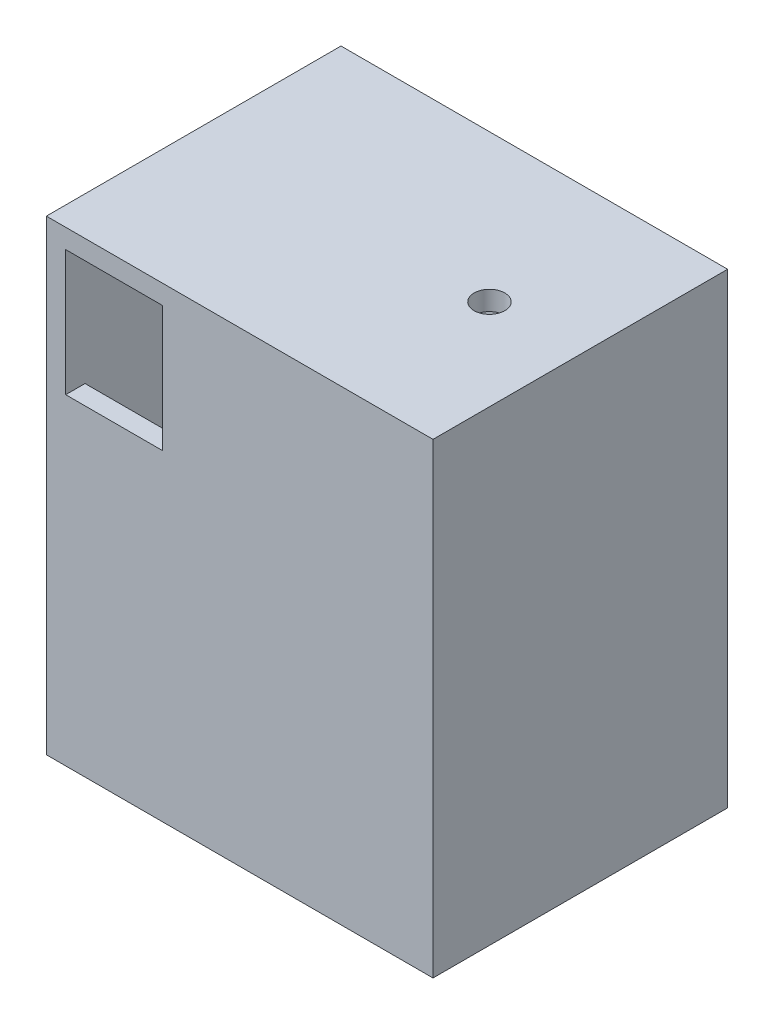
SolidWorks part; units mm, degrees
ref_plane "Front Plane" through (0, 0, 0) normal (0, 0, 1) x (1, 0, 0)
ref_plane "Top Plane" through (0, 0, 0) normal (0, 1, 0) x (1, 0, 0)
ref_plane "Right Plane" through (0, 0, 0) normal (1, 0, 0) x (0, 0, -1)
sketch "Sketch1" plane through (0, 0, 0) normal (0, 1, 0) x (1, 0, 0)
  line L1 (-200, 152.4) -> (200, 152.4)
  line L2 (-200, 152.4) -> (-200, -152.4)
  line L3 (-200, -152.4) -> (200, -152.4)
  line L4 (200, 152.4) -> (200, -152.4)
  line L5 (-200, 152.4) -> (200, -152.4) construction
  line L6 (-200, -152.4) -> (200, 152.4) construction
  point P0 (0, 0)
  dimension "D1" = 400
  dimension "D2" = 304.8
extrude "Boss-Extrude1" add sketch "Sketch1" along normal blind 482.6 contours L2 L3 L4 L1
shell "Shell1" thickness 20
sketch "Sketch2" plane through (0, 482.6, 0) normal (0, 1, 0) x (1, 0, 0)
  line L0 (-55, 0) -> (55, 0) construction
  line L1 (200, 152.4) -> (200, -152.4) construction
  circle A0 centre (106, 0) radius 15.9047
  dimension "D1" = 94
extrude "Cut-Extrude1" cut sketch "Sketch2" against normal up to next
sketch "Sketch3" plane through (0, 0, 152.4) normal (0, 0, 1) x (1, 0, 0)
  line L2 (-200, 482.6) -> (-200, 0) construction
  line L3 (-180, 462.6) -> (-80, 462.6)
  line L4 (-180, 462.6) -> (-180, 332.6)
  line L5 (-180, 332.6) -> (-80, 332.6)
  line L6 (-80, 462.6) -> (-80, 332.6)
  line L7 (-200, 482.6) -> (200, 482.6) construction
  dimension "D2" = 20
  dimension "D1" = 20
  dimension "D3" = 100
  dimension "D4" = 130
extrude "Cut-Extrude2" cut sketch "Sketch3" against normal blind 50
sketch "Sketch4" plane through (0, 0, 0) normal (0, -1, 0) x (1, 0, 0)
  line L0 (220, 0) -> (-220, 0) construction
  line L1 (-90, 40) -> (-30, 40)
  line L2 (-90, 40) -> (-90, -40)
  line L3 (-90, -40) -> (-30, -40)
  line L4 (-30, 40) -> (-30, -40)
  line L5 (-90, 40) -> (-30, -40) construction
  line L6 (-90, -40) -> (-30, 40) construction
  line L7 (-200, -152.4) -> (-200, 152.4) construction
  point P0 (-60, 0)
  dimension "D1" = 170
  dimension "D2" = 80
  dimension "D3" = 60
extrude "Cut-Extrude3" cut sketch "Sketch4" against normal blind 30
